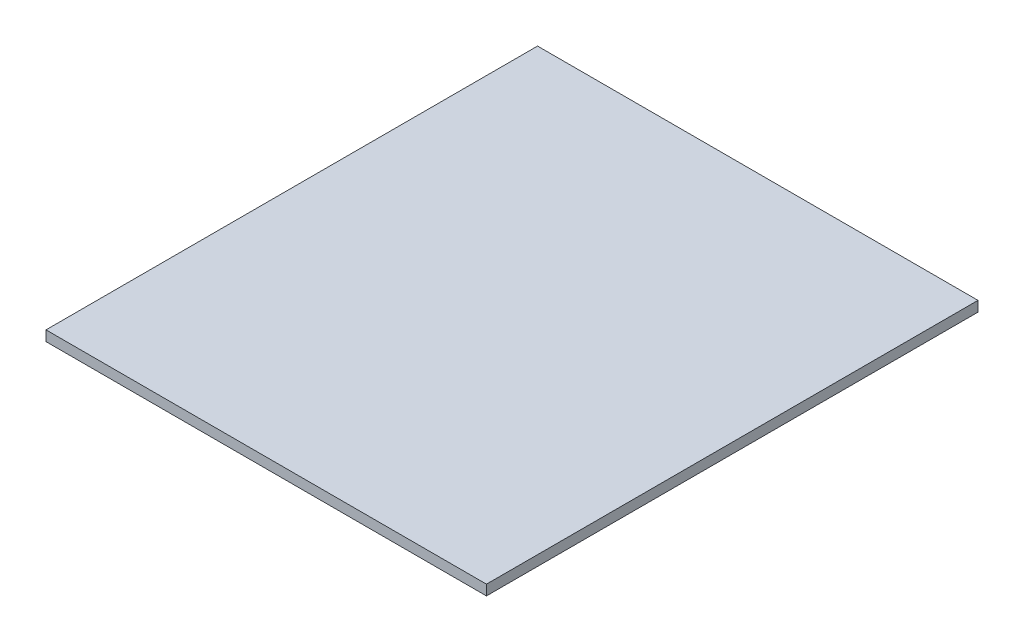
SolidWorks part; units mm, degrees
ref_plane "Front Plane" through (0, 0, 0) normal (0, 0, 1) x (1, 0, 0)
ref_plane "Top Plane" through (0, 0, 0) normal (0, 1, 0) x (1, 0, 0)
ref_plane "Right Plane" through (0, 0, 0) normal (1, 0, 0) x (0, 0, -1)
sketch "Sketch1" plane through (0, 0, 0) normal (0, 1, 0) x (1, 0, 0)
  line L1 (-172.4, 192.4) -> (172.4, 192.4)
  line L2 (-172.4, 192.4) -> (-172.4, -192.4)
  line L3 (-172.4, -192.4) -> (172.4, -192.4)
  line L4 (172.4, 192.4) -> (172.4, -192.4)
  line L5 (-172.4, 192.4) -> (172.4, -192.4) construction
  line L6 (-172.4, -192.4) -> (172.4, 192.4) construction
  point P0 (0, 0)
  dimension "D1" = 384.8
  dimension "D2" = 344.8
extrude "Boss-Extrude1" add sketch "Sketch1" along normal mid plane 8
